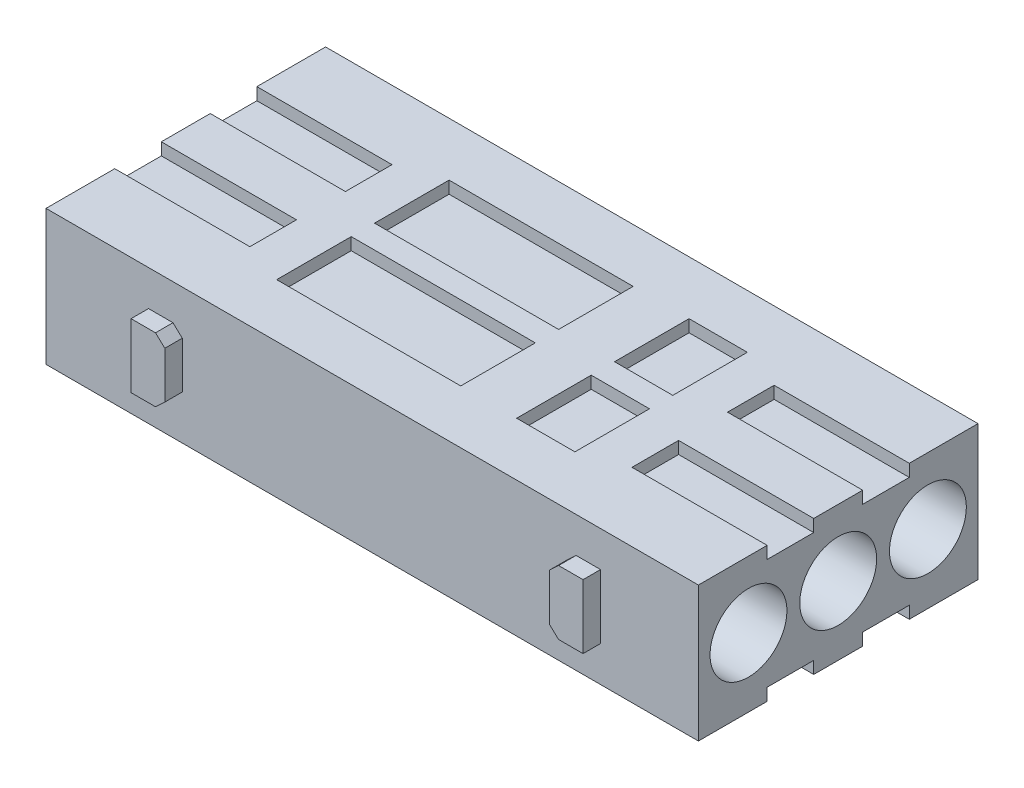
SolidWorks part; units mm, degrees
ref_plane "Front Plane" through (0, 0, 0) normal (0, 0, 1) x (1, 0, 0)
ref_plane "Top Plane" through (0, 0, 0) normal (0, 1, 0) x (1, 0, 0)
ref_plane "Right Plane" through (0, 0, 0) normal (1, 0, 0) x (0, 0, -1)
sketch "Sketch1" plane through (0, 0, 0) normal (0, 1, 0) x (1, 0, 0)
  line L1 (0, 0) -> (71.12, 0)
  line L2 (0, 0) -> (0, 30.48)
  line L3 (0, 30.48) -> (71.12, 30.48)
  line L4 (71.12, 0) -> (71.12, 30.48)
  dimension "D1" = 71.12
  dimension "D2" = 30.48
extrude "Boss-Extrude1" add sketch "Sketch1" along normal blind 14.732
sketch "Sketch2" plane through (71.12, 0, 0) normal (1, 0, 0) x (0, 0, -1)
  line L0 (0, 14.732) -> (0, 0) construction
  line L1 (0, 14.732) -> (30.48, 14.732) construction
  line L4 (30.48, 14.732) -> (30.48, 0) construction
  circle A0 centre (15.24, 7.493) radius 4.191
  circle A1 centre (25.019, 7.493) radius 4.191
  circle A2 centre (5.461, 7.493) radius 4.191
  dimension "D1" = 8.382
  dimension "D3" = 7.239
  dimension "D2" = 5.461
  dimension "D4" = 7.239
  dimension "D5" = 7.239
  dimension "D6" = 5.461
  dimension "D7" = 15.24
extrude "Cut-Extrude1" cut sketch "Sketch2" against normal blind 12.7
sketch "Sketch3" plane through (0, 0, 0) normal (-1, 0, 0) x (0, 0, 1)
  line L0 (-30.48, 14.732) -> (-30.48, 0) construction
  line L1 (0, 14.732) -> (0, 0) construction
  line L2 (-30.48, 14.732) -> (0, 14.732) construction
  circle A0 centre (-15.24, 7.493) radius 4.191
  circle A1 centre (-5.461, 7.493) radius 4.191
  circle A2 centre (-25.019, 7.493) radius 4.191
  dimension "D1" = 8.382
  dimension "D2" = 5.461
  dimension "D3" = 5.461
  dimension "D4" = 15.24
  dimension "D5" = 7.239
  dimension "D6" = 7.239
  dimension "D7" = 7.239
extrude "Cut-Extrude2" cut sketch "Sketch3" against normal blind 25.4
sketch "Sketch4" plane through (0, 14.732, 0) normal (0, 1, 0) x (1, 0, 0)
  line L0 (71.12, 0) -> (71.12, 30.48) construction
  line L1 (71.12, 22.987) -> (56.388, 22.987)
  line L2 (71.12, 22.987) -> (71.12, 17.907)
  line L3 (71.12, 17.907) -> (56.388, 17.907)
  line L4 (56.388, 22.987) -> (56.388, 17.907)
  line L5 (0, 30.48) -> (0, 0) construction
  line L6 (71.12, 12.573) -> (56.388, 12.573)
  line L7 (71.12, 12.573) -> (71.12, 7.493)
  line L8 (71.12, 7.493) -> (56.388, 7.493)
  line L9 (56.388, 12.573) -> (56.388, 7.493)
  line L10 (51.816, 24.638) -> (45.466, 24.638)
  line L11 (51.816, 24.638) -> (51.816, 16.51)
  line L12 (51.816, 16.51) -> (45.466, 16.51)
  line L13 (45.466, 24.638) -> (45.466, 16.51)
  line L14 (51.816, 13.97) -> (45.466, 13.97)
  line L15 (51.816, 13.97) -> (51.816, 5.842)
  line L16 (51.816, 5.842) -> (45.466, 5.842)
  line L17 (45.466, 13.97) -> (45.466, 5.842)
  line L18 (39.37, 24.638) -> (19.304, 24.638)
  line L19 (39.37, 24.638) -> (39.37, 16.51)
  line L20 (39.37, 16.51) -> (19.304, 16.51)
  line L21 (19.304, 24.638) -> (19.304, 16.51)
  line L22 (39.37, 13.97) -> (19.304, 13.97)
  line L23 (39.37, 13.97) -> (39.37, 5.842)
  line L24 (39.37, 5.842) -> (19.304, 5.842)
  line L25 (19.304, 13.97) -> (19.304, 5.842)
  line L26 (0, 22.987) -> (14.732, 22.987)
  line L27 (0, 22.987) -> (0, 17.907)
  line L28 (0, 17.907) -> (14.732, 17.907)
  line L29 (14.732, 22.987) -> (14.732, 17.907)
  line L30 (71.12, 30.48) -> (0, 30.48) construction
  line L31 (0, 12.573) -> (14.732, 12.573)
  line L32 (0, 12.573) -> (0, 7.493)
  line L33 (0, 7.493) -> (14.732, 7.493)
  line L34 (14.732, 12.573) -> (14.732, 7.493)
  line L35 (0, 0) -> (71.12, 0) construction
  dimension "D1" = 5.08
  dimension "D2" = 7.493
  dimension "D3" = 5.08
  dimension "D4" = 7.493
  dimension "D5" = 14.732
  dimension "D6" = 14.732
  dimension "D7" = 7.493
  dimension "D8" = 7.493
  dimension "D9" = 14.732
  dimension "D10" = 14.732
  dimension "D11" = 5.08
  dimension "D12" = 5.08
  dimension "D13" = 8.128
  dimension "D14" = 8.128
  dimension "D15" = 5.842
  dimension "D16" = 5.842
  dimension "D17" = 5.842
  dimension "D18" = 5.842
  dimension "D19" = 20.066
  dimension "D20" = 20.066
  dimension "D21" = 19.304
  dimension "D22" = 19.304
  dimension "D23" = 6.35
  dimension "D24" = 6.35
  dimension "D25" = 8.128
  dimension "D26" = 8.128
  dimension "D27" = 19.304
  dimension "D28" = 19.304
extrude "Cut-Extrude3" cut sketch "Sketch4" against normal blind 1.3335
sketch "Sketch5" plane through (0, 0, 0) normal (0, 0, 1) x (1, 0, 0)
  line L0 (60.452, 3.8735) -> (60.452, 10.8585)
  line L1 (60.452, 10.8585) -> (57.785, 10.8585)
  line L2 (57.785, 10.8585) -> (56.769, 9.906)
  line L3 (56.769, 9.906) -> (56.769, 4.826)
  line L4 (56.769, 4.826) -> (57.785, 3.8735)
  line L5 (57.785, 3.8735) -> (60.452, 3.8735)
  line L7 (71.12, 14.732) -> (71.12, 0) construction
  line L8 (59.1185, 10.8585) -> (59.1185, 14.732) construction
  line L9 (0, 14.732) -> (71.12, 14.732) construction
  line L10 (60.0616, 3.8735) -> (60.0616, 0) construction
  line L11 (0, 0) -> (71.12, 0) construction
  line L12 (35.814, 14.732) -> (35.814, 0) construction
  line L13 (0, 14.732) -> (0, 0) construction
  line L14 (14.605, 7.399) -> (10.922, 7.399) construction
  line L15 (13.843, 3.8735) -> (11.176, 3.8735)
  line L16 (14.859, 4.826) -> (13.843, 3.8735)
  line L17 (14.859, 9.906) -> (14.859, 4.826)
  line L18 (13.843, 10.8585) -> (14.859, 9.906)
  line L19 (11.176, 10.8585) -> (13.843, 10.8585)
  line L20 (11.176, 3.8735) -> (11.176, 10.8585)
  dimension "D1" = 6.985
  dimension "D2" = 5.08
  dimension "D3" = 2.667
  dimension "D4" = 10.668
  dimension "D5" = 35.814
  dimension "D6" = 3.683
extrude "Boss-Extrude2" add sketch "Sketch5" along normal blind 1.905
sketch "Sketch6" plane through (0, 0, -30.48) normal (0, 0, -1) x (-1, 0, 0)
  line L0 (-60.452, 11.938) -> (-60.452, 2.794)
  line L1 (-60.452, 2.794) -> (-57.785, 2.794)
  line L2 (-57.785, 2.794) -> (-56.769, 3.937)
  line L3 (-56.769, 3.937) -> (-56.769, 10.795)
  line L4 (-56.769, 10.795) -> (-57.785, 11.938)
  line L5 (-57.785, 11.938) -> (-60.452, 11.938)
  line L6 (-71.12, 14.732) -> (-71.12, 0) construction
  line L7 (-59.5499, 2.794) -> (-59.5499, 0) construction
  line L8 (-71.12, 0) -> (0, 0) construction
  line L9 (-60.2448, 11.938) -> (-60.2448, 14.732) construction
  line L10 (-71.12, 14.732) -> (0, 14.732) construction
  line L11 (-35.56, 0) -> (-35.56, 14.732) construction
  line L13 (-10.8752, 11.938) -> (-10.8752, 14.732) construction
  line L14 (-11.5701, 2.794) -> (-11.5701, 0) construction
  line L15 (-13.335, 11.938) -> (-10.668, 11.938)
  line L16 (-14.351, 10.795) -> (-13.335, 11.938)
  line L17 (-14.351, 3.937) -> (-14.351, 10.795)
  line L18 (-13.335, 2.794) -> (-14.351, 3.937)
  line L19 (-10.668, 2.794) -> (-13.335, 2.794)
  line L20 (-10.668, 11.938) -> (-10.668, 2.794)
  line L21 (0, 14.732) -> (0, 0) construction
  dimension "D1" = 10.668
  dimension "D2" = 9.144
  dimension "D3" = 3.683
  dimension "D4" = 2.667
  dimension "D5" = 6.858
  dimension "D6" = 10.668
extrude "Boss-Extrude3" add sketch "Sketch6" along normal blind 1.905
sketch "Sketch7" plane through (0, 0, 0) normal (0, -1, 0) x (1, 0, 0)
  line L0 (0, -30.48) -> (0, 0) construction
  line L1 (0, -22.987) -> (14.732, -22.987)
  line L2 (0, -22.987) -> (0, -17.907)
  line L3 (0, -17.907) -> (14.732, -17.907)
  line L4 (14.732, -22.987) -> (14.732, -17.907)
  line L5 (71.12, 0) -> (71.12, -30.48) construction
  line L6 (0, -12.573) -> (14.732, -12.573)
  line L7 (0, -12.573) -> (0, -7.493)
  line L8 (0, -7.493) -> (14.732, -7.493)
  line L9 (14.732, -12.573) -> (14.732, -7.493)
  line L10 (19.304, -24.638) -> (39.37, -24.638)
  line L11 (19.304, -24.638) -> (19.304, -16.51)
  line L12 (19.304, -16.51) -> (39.37, -16.51)
  line L13 (39.37, -24.638) -> (39.37, -16.51)
  line L14 (19.304, -13.97) -> (39.37, -13.97)
  line L15 (19.304, -13.97) -> (19.304, -5.842)
  line L16 (19.304, -5.842) -> (39.37, -5.842)
  line L17 (39.37, -13.97) -> (39.37, -5.842)
  line L18 (45.466, -24.638) -> (51.816, -24.638)
  line L19 (45.466, -24.638) -> (45.466, -16.51)
  line L20 (45.466, -16.51) -> (51.816, -16.51)
  line L21 (51.816, -24.638) -> (51.816, -16.51)
  line L22 (45.466, -13.97) -> (51.816, -13.97)
  line L23 (45.466, -13.97) -> (45.466, -5.842)
  line L24 (45.466, -5.842) -> (51.816, -5.842)
  line L25 (51.816, -13.97) -> (51.816, -5.842)
  line L26 (71.12, -22.987) -> (56.388, -22.987)
  line L27 (71.12, -22.987) -> (71.12, -17.907)
  line L28 (71.12, -17.907) -> (56.388, -17.907)
  line L29 (56.388, -22.987) -> (56.388, -17.907)
  line L30 (71.12, -30.48) -> (0, -30.48) construction
  line L31 (71.12, -12.573) -> (56.388, -12.573)
  line L32 (71.12, -12.573) -> (71.12, -7.493)
  line L33 (71.12, -7.493) -> (56.388, -7.493)
  line L34 (56.388, -12.573) -> (56.388, -7.493)
  line L35 (0, 0) -> (71.12, 0) construction
  point P41 (0, 0)
  point P42 (0, 0)
  point P43 (0, 0)
  dimension "D6" = 14.732
  dimension "D13" = 8.128
  dimension "D1" = 6.35
  dimension "D2" = 6.35
  dimension "D3" = 19.304
  dimension "D4" = 19.304
  dimension "D5" = 5.08
  dimension "D7" = 5.08
  dimension "D8" = 14.732
  dimension "D9" = 7.493
  dimension "D10" = 7.493
  dimension "D11" = 5.842
  dimension "D12" = 8.128
  dimension "D14" = 5.842
  dimension "D15" = 20.066
  dimension "D16" = 20.066
  dimension "D17" = 8.128
  dimension "D18" = 8.128
  dimension "D19" = 19.304
  dimension "D20" = 19.304
  dimension "D21" = 5.842
  dimension "D22" = 5.842
  dimension "D24" = 5.08
  dimension "D25" = 14.732
  dimension "D26" = 14.732
  dimension "D27" = 7.493
  dimension "D23" = 5.08
  dimension "D28" = 7.493
extrude "Cut-Extrude4" cut sketch "Sketch7" against normal blind 1.3335
equation "\"a\"=0.295"
equation "\"D2@Sketch4\"=\"a\""
equation "\"D4@Sketch4\"=\"a\""
equation "\"b\"=0.58"
equation "\"D5@Sketch4\"=\"b\""
equation "\"D6@Sketch4\"=\"b\""
equation "\"D7@Sketch4\"=\"a\""
equation "\"D8@Sketch4\"=\"a\""
equation "\"D9@Sketch4\"=\"b\""
equation "\"D10@Sketch4\"=\"b\""
equation "\"d\"=0.32"
equation "\"D13@Sketch4\"=\"d\""
equation "\"D14@Sketch4\"=\"d\""
equation "\"f\"=0.23"
equation "\"D15@Sketch4\"=\"f\""
equation "\"D16@Sketch4\"=\"f\""
equation "\"D17@Sketch4\"=\"f\""
equation "\"D18@Sketch4\"=\"f\""
equation "\"D25@Sketch4\"=\"d\""
equation "\"D26@Sketch4\"=\"d\""
equation "\"D6@Sketch7\"=\"b\""
equation "\"D8@Sketch7\"=\"b\""
equation "\"D9@Sketch7\"=\"a\""
equation "\"D10@Sketch7\"=\"a\""
equation "\"D11@Sketch7\"=\"f\""
equation "\"D12@Sketch7\"=\"d\""
equation "\"D13@Sketch7\"=\"d\""
equation "\"D14@Sketch7\"=\"f\""
equation "\"D17@Sketch7\"=\"d\""
equation "\"D18@Sketch7\"=\"d\""
equation "\"D21@Sketch7\"=\"f\""
equation "\"D22@Sketch7\"=\"f\""
equation "\"D25@Sketch7\"=\"b\""
equation "\"D26@Sketch7\"=\"b\""
equation "\"D27@Sketch7\"=\"a\""
equation "\"D28@Sketch7\"=\"a\""
